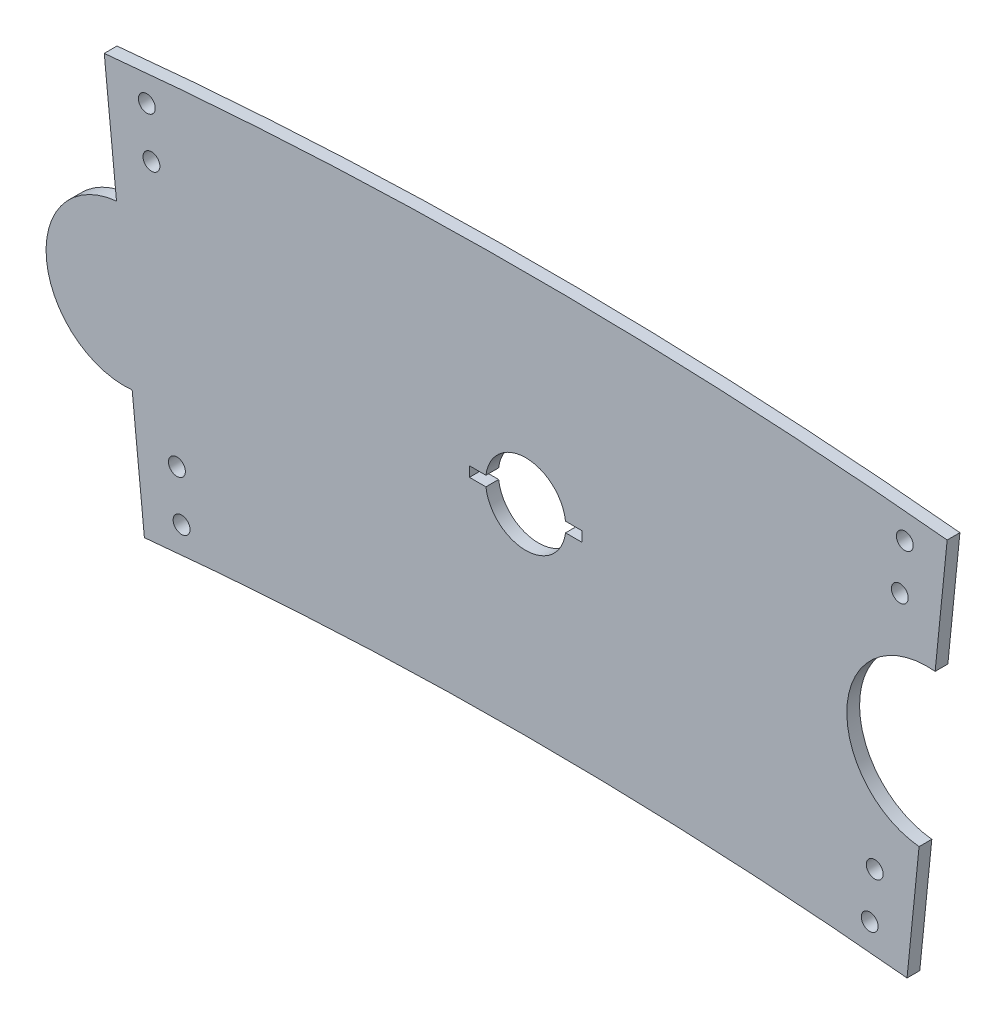
SolidWorks part; units mm, degrees
material "Balsa"
ref_plane "Front Plane" through (0, 0, 0) normal (0, 0, 1) x (1, 0, 0)
ref_plane "Top Plane" through (0, 0, 0) normal (0, 1, 0) x (1, 0, 0)
ref_plane "Right Plane" through (0, 0, 0) normal (1, 0, 0) x (0, 0, -1)
sketch "Sketch1" plane through (0, 0, 0) normal (0, 0, 1) x (1, 0, 0)
  line L0 (-105, 44.7368) -> (-101.95, 14.3897)
  line L1 (-98.05, -24.4148) -> (-95, -54.7619)
  line L6 (-14.0216, 1.25) -> (-9.9216, 1.25)
  line L7 (-14.0216, -1.25) -> (-14.0216, 1.25)
  line L8 (-9.9216, -1.25) -> (-14.0216, -1.25)
  line L9 (14.0216, -1.25) -> (9.9216, -1.25)
  line L10 (14.0216, 1.25) -> (14.0216, -1.25)
  line L11 (9.9216, 1.25) -> (14.0216, 1.25)
  line L13 (0, 0) -> (0, -1000) construction
  line L14 (0, 0) -> (192.465, 0) construction
  line L15 (105, 44.7368) -> (0, -1000) construction
  line L16 (0, -1000) -> (-105, 44.7368) construction
  line L22 (95, -54.7619) -> (98, -24.9123)
  line L23 (105, 44.7368) -> (102, 14.8872)
  line L24 (0, 0) -> (-18.493, 0) construction
  circle A0 centre (0, 0) radius 7.5 construction
  circle A1 centre (0, 0) radius 100 construction
  arc A4 (9.9216, 1.25) -> (-9.9216, 1.25) centre (0, 0) ccw
  arc A5 (-9.9216, -1.25) -> (9.9216, -1.25) centre (0, 0) ccw
  arc A6 (102, 14.8872) -> (98, -24.9123) centre (100, -5.0126) ccw
  circle A8 centre (0, -1000) radius 1000 construction
  arc A9 (95, -54.7619) -> (-95, -54.7619) centre (0, -1000) ccw
  arc A10 (105, 44.7368) -> (-105, 44.7368) centre (0, -1000) ccw
  arc A11 (-101.95, 14.3897) -> (-98.05, -24.4148) centre (-100, -5.0126) ccw
  point P8 (0, 50)
  point P9 (0, -50)
  point P10 (-100, -5.0126)
  point P20 (100, -5.0126)
  dimension "D1" = 200
  dimension "D2" = 2000
  dimension "D4" = 20
  dimension "D5" = 2.5
  dimension "D7" = 10
  dimension "D8" = 39
  dimension "D3" = 50
  dimension "D6" = 4.1
extrude "Boss-Extrude1" add sketch "Sketch1" along normal blind 3.175
sketch "Sketch3" plane through (0, 0, 3.175) normal (0, 0, 1) x (1, 0, 0)
  circle A1 centre (-94.3968, 39.2339) radius 2.1
  circle A2 centre (-93.2395, 27.2898) radius 2.1
  circle A3 centre (-86.8968, -35.3902) radius 2.1
  circle A4 centre (-85.7395, -47.3343) radius 2.1
  circle A5 centre (85.704, -47.259) radius 2.1
  circle A6 centre (86.9466, -35.3236) radius 2.1
  circle A7 centre (93.204, 27.365) radius 2.1
  circle A8 centre (94.4466, 39.3005) radius 2.1
  point P2 (-93.2395, 27.2898)
  point P3 (-94.3968, 39.2339)
  point P4 (-85.7395, -47.3343)
  point P5 (-86.8968, -35.3902)
  point P6 (93.204, 27.365)
  point P7 (94.4466, 39.3005)
  point P8 (86.9466, -35.3236)
  point P9 (85.704, -47.259)
extrude "Cut-Extrude1" cut sketch "Sketch3" against normal blind 10
